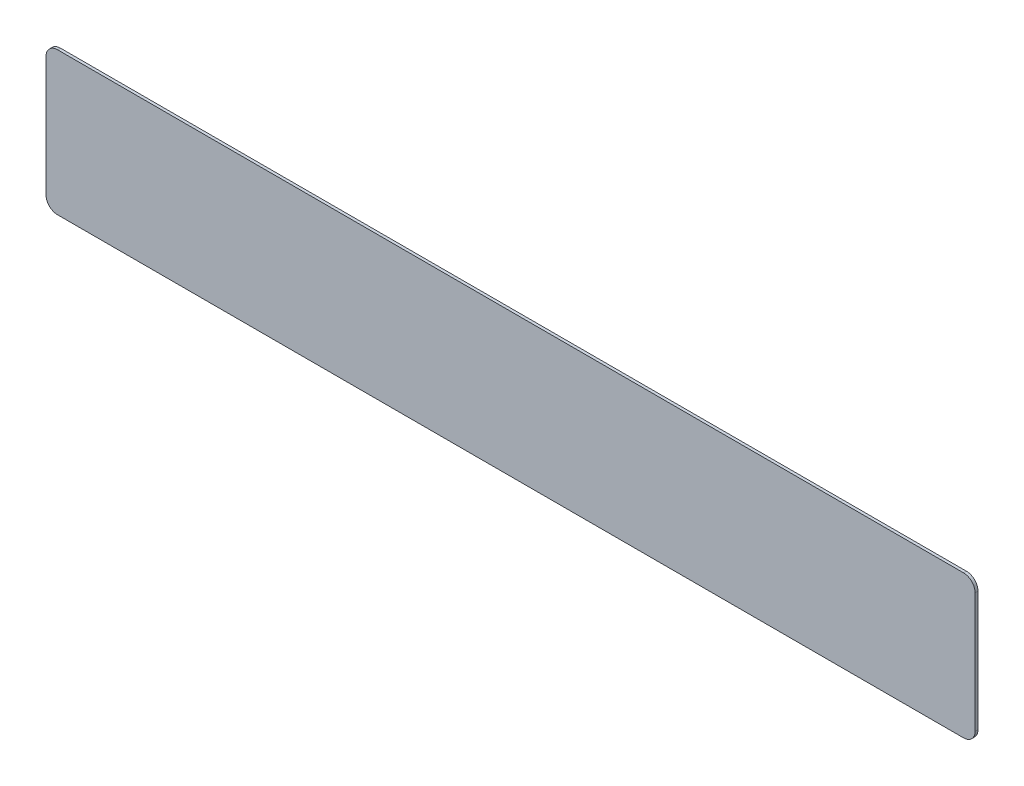
SolidWorks part; units mm, degrees
ref_plane "Front Plane" through (0, 0, 0) normal (0, 0, 1) x (1, 0, 0)
ref_plane "Top Plane" through (0, 0, 0) normal (0, 1, 0) x (1, 0, 0)
ref_plane "Right Plane" through (0, 0, 0) normal (1, 0, 0) x (0, 0, -1)
sketch "Sketch1" plane through (0, 0, 0) normal (0, 0, 1) x (1, 0, 0)
  line L1 (-316.9013, -50) -> (316.9013, -50)
  line L2 (-325, -41.9013) -> (-325, 41.9013)
  line L3 (-316.9013, 50) -> (316.9013, 50)
  line L4 (325, -41.9013) -> (325, 41.9013)
  line L5 (-325, -50) -> (325, 50) construction
  line L6 (-325, 50) -> (325, -50) construction
  arc A0 (316.9013, -50) -> (325, -41.9013) centre (316.9013, -41.9013) ccw
  arc A1 (325, 41.9013) -> (316.9013, 50) centre (316.9013, 41.9013) ccw
  arc A2 (-316.9013, -50) -> (-325, -41.9013) centre (-316.9013, -41.9013) cw
  arc A3 (-325, 41.9013) -> (-316.9013, 50) centre (-316.9013, 41.9013) cw
  point P0 (0, 0)
  dimension "D3" = 8.0987
  dimension "D1" = 100
  dimension "D2" = 650
extrude "Boss-Extrude1" add sketch "Sketch1" along normal blind 2
